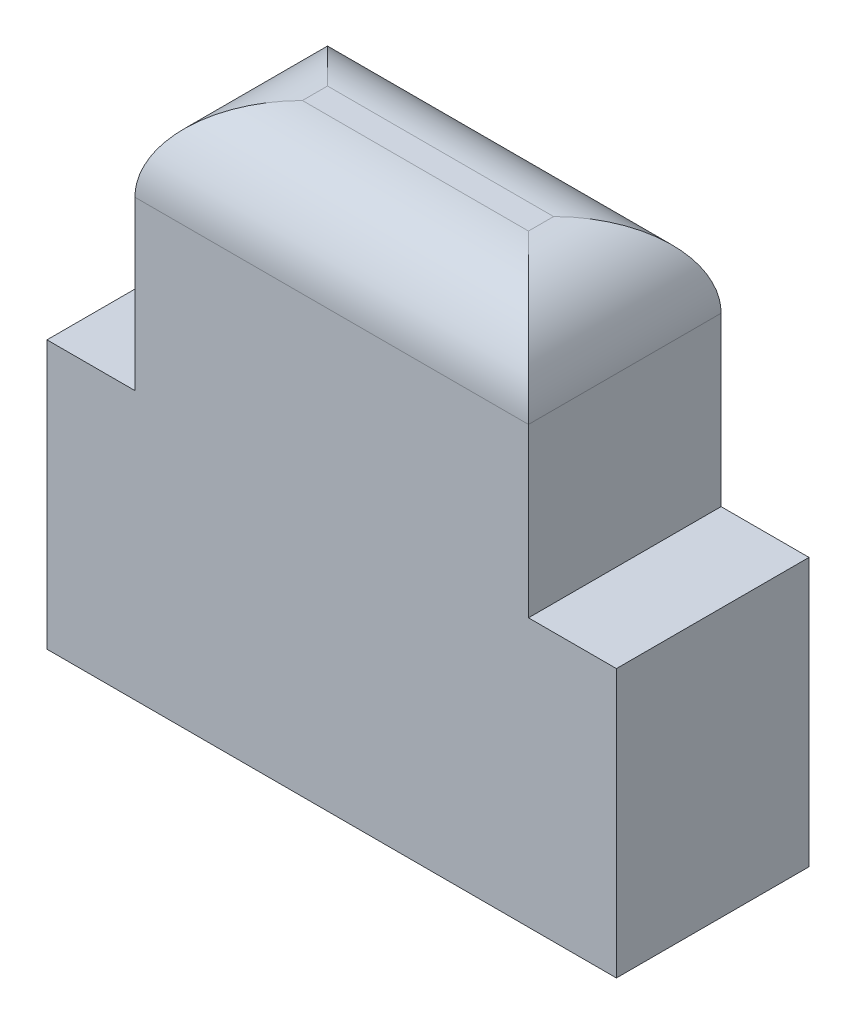
SolidWorks part; units mm, degrees
ref_plane "前视基准面" through (0, 0, 0) normal (0, 0, 1) x (1, 0, 0)
ref_plane "上视基准面" through (0, 0, 0) normal (0, 1, 0) x (1, 0, 0)
ref_plane "右视基准面" through (0, 0, 0) normal (1, 0, 0) x (0, 0, -1)
sketch "Sketch1" plane through (0, 0, 0) normal (0, 1, 0) x (1, 0, 0)
  line L1 (-3.4, 1.15) -> (3.4, 1.15)
  line L2 (-3.4, 1.15) -> (-3.4, -1.15)
  line L3 (-3.4, -1.15) -> (3.4, -1.15)
  line L4 (3.4, 1.15) -> (3.4, -1.15)
  line L5 (-3.4, 1.15) -> (3.4, -1.15) construction
  line L6 (-3.4, -1.15) -> (3.4, 1.15) construction
  point P0 (0, 0)
  dimension "D1" = 6.8
  dimension "D2" = 2.3
extrude "Boss-Extrude1" add sketch "Sketch1" along normal blind 3.2
sketch "Sketch2" plane through (0, 3.2, 0) normal (0, 1, 0) x (1, 0, 0)
  line L0 (3.4, 1.15) -> (-3.4, 1.15) construction
  line L1 (-2.35, -1.15) -> (2.35, -1.15)
  line L2 (-2.35, -1.15) -> (-2.35, 1.15)
  line L3 (-2.35, 1.15) -> (2.35, 1.15)
  line L4 (2.35, -1.15) -> (2.35, 1.15)
  line L5 (-2.35, -1.15) -> (2.35, 1.15) construction
  line L6 (-2.35, 1.15) -> (2.35, -1.15) construction
  point P0 (0, 0)
  dimension "D1" = 4.7
extrude "Boss-Extrude2" add sketch "Sketch2" along normal blind 3
fillet "Fillet1" radius 1 4 edges at (0, 6.2, -1.15) (2.35, 6.2, 0) (0, 6.2, 1.15) (-2.35, 6.2, 0)
